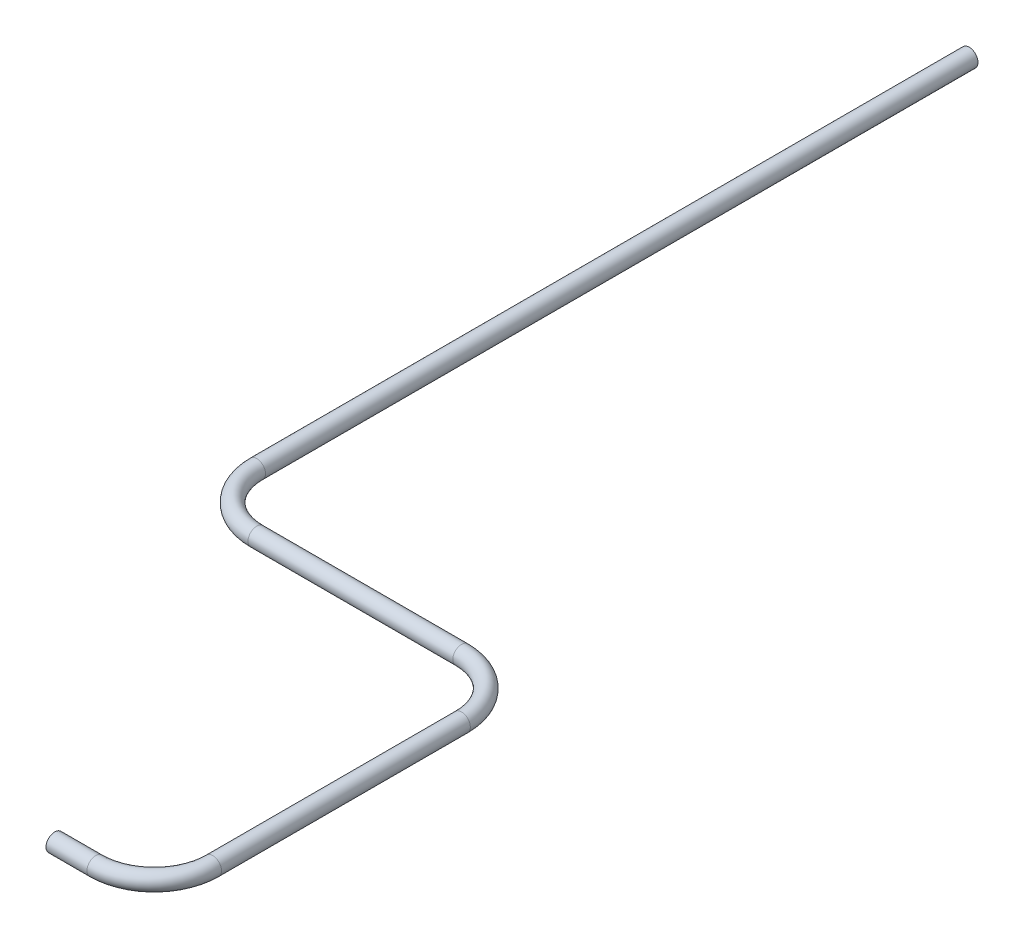
SolidWorks part; units mm, degrees
ref_plane "Alzado" through (0, 0, 0) normal (0, 0, 1) x (1, 0, 0)
ref_plane "Planta" through (0, 0, 0) normal (0, 1, 0) x (1, 0, 0)
ref_plane "Vista lateral" through (0, 0, 0) normal (1, 0, 0) x (0, 0, -1)
sketch "Croquis1" plane through (0, 0, 0) normal (0, 1, 0) x (1, 0, 0)
  line L0 (0, 0) -> (0, -121.77)
  line L1 (10, -131.77) -> (45, -131.77)
  line L2 (55, -141.77) -> (55, -184.29)
  line L3 (45, -194.29) -> (38, -194.29)
  arc A0 (55, -141.77) -> (45, -131.77) centre (45, -141.77) ccw
  arc A1 (55, -184.29) -> (45, -194.29) centre (45, -184.29) cw
  arc A2 (0, -121.77) -> (10, -131.77) centre (10, -121.77) ccw
  point P8 (55, -131.77)
  point P11 (55, -194.29)
  point P14 (0, -131.77)
  dimension "D5" = 10
  dimension "D6" = 10
  dimension "D7" = 10
  dimension "D1" = 131.77
  dimension "D2" = 55
  dimension "D3" = 62.52
  dimension "D4" = 17
sweep "Barrer2" add path "Croquis1" circular profile diameter 3 parameters "D3"=3
